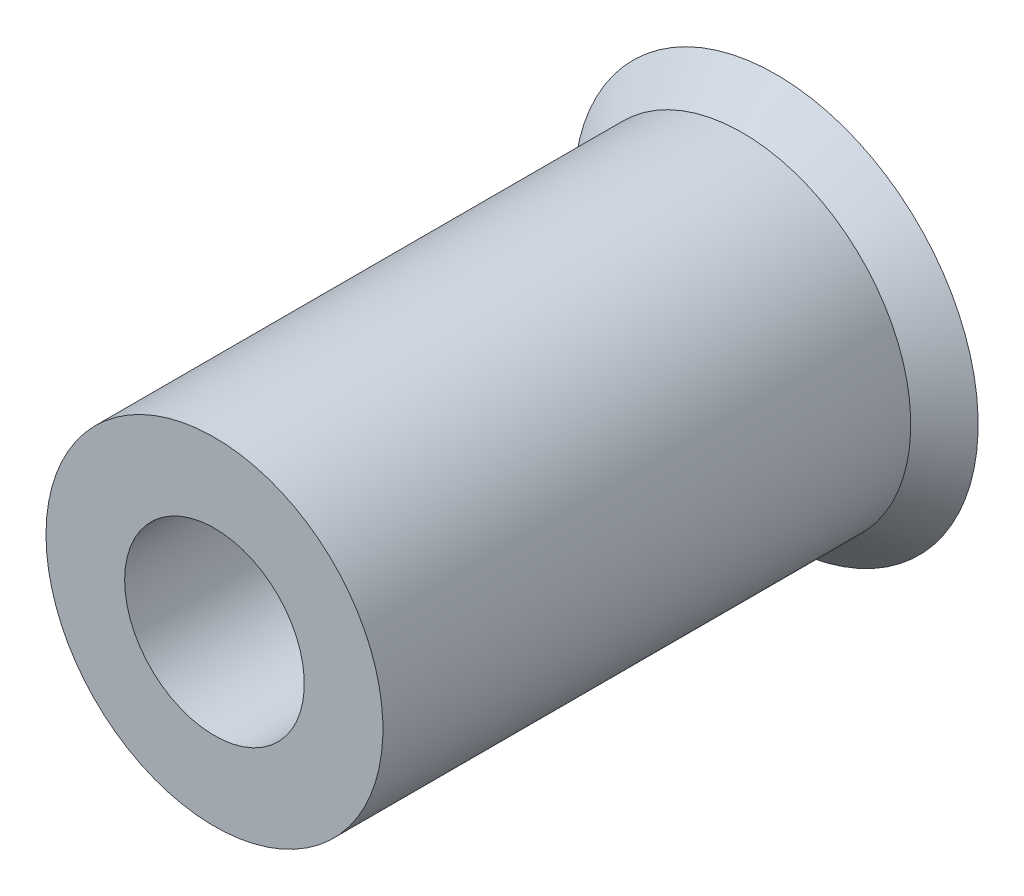
SolidWorks part; units mm, degrees
material "AISI 304"
ref_plane "前视基准面" through (0, 0, 0) normal (0, 0, 1) x (1, 0, 0)
ref_plane "上视基准面" through (0, 0, 0) normal (0, 1, 0) x (1, 0, 0)
ref_plane "右视基准面" through (0, 0, 0) normal (1, 0, 0) x (0, 0, -1)
sketch "草图1" plane through (0, 0, 0) normal (1, 0, 0) x (0, 0, -1)
  line L0 (0, 0) -> (-38.8093, 0) construction
  line L2 (-10, 1.6) -> (0, 1.6)
  line L4 (0, 1.6) -> (0, 3.6)
  line L5 (0, 3.6) -> (-0.6, 3)
  line L6 (-0.6, 3) -> (-10, 3)
  line L7 (-10, 3) -> (-10, 1.6)
  dimension "D1" = 45
  dimension "L" = 10
  dimension "D" = 6
  dimension "k" = 0.6
  dimension "底孔直径" = 3.2
revolve "旋转1" add sketch "草图1" angle 360 about L0
cosmetic thread "装饰螺纹线1" parameters "D1"=4.5, "D2"=4.2
